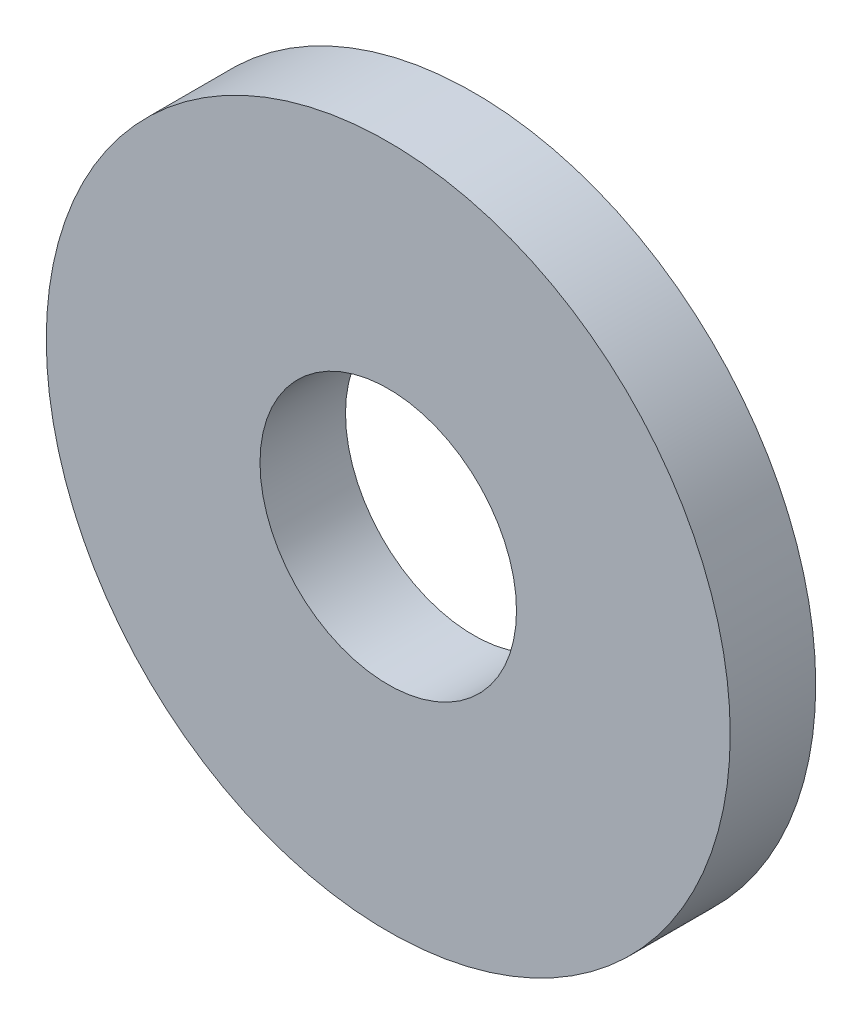
SolidWorks part; units mm, degrees
material "亚克力"
ref_plane "前视基准面" through (0, 0, 0) normal (0, 0, 1) x (1, 0, 0)
ref_plane "上视基准面" through (0, 0, 0) normal (0, 1, 0) x (1, 0, 0)
ref_plane "右视基准面" through (0, 0, 0) normal (1, 0, 0) x (0, 0, -1)
sketch "草图1" plane through (0, 0, 0) normal (0, 0, 1) x (1, 0, 0)
  circle A0 centre (0, 0) radius 3
  circle A1 centre (0, 0) radius 8
  dimension "D1" = 6
  dimension "D2" = 16
extrude "凸台-拉伸1" add sketch "草图1" along normal blind 2
